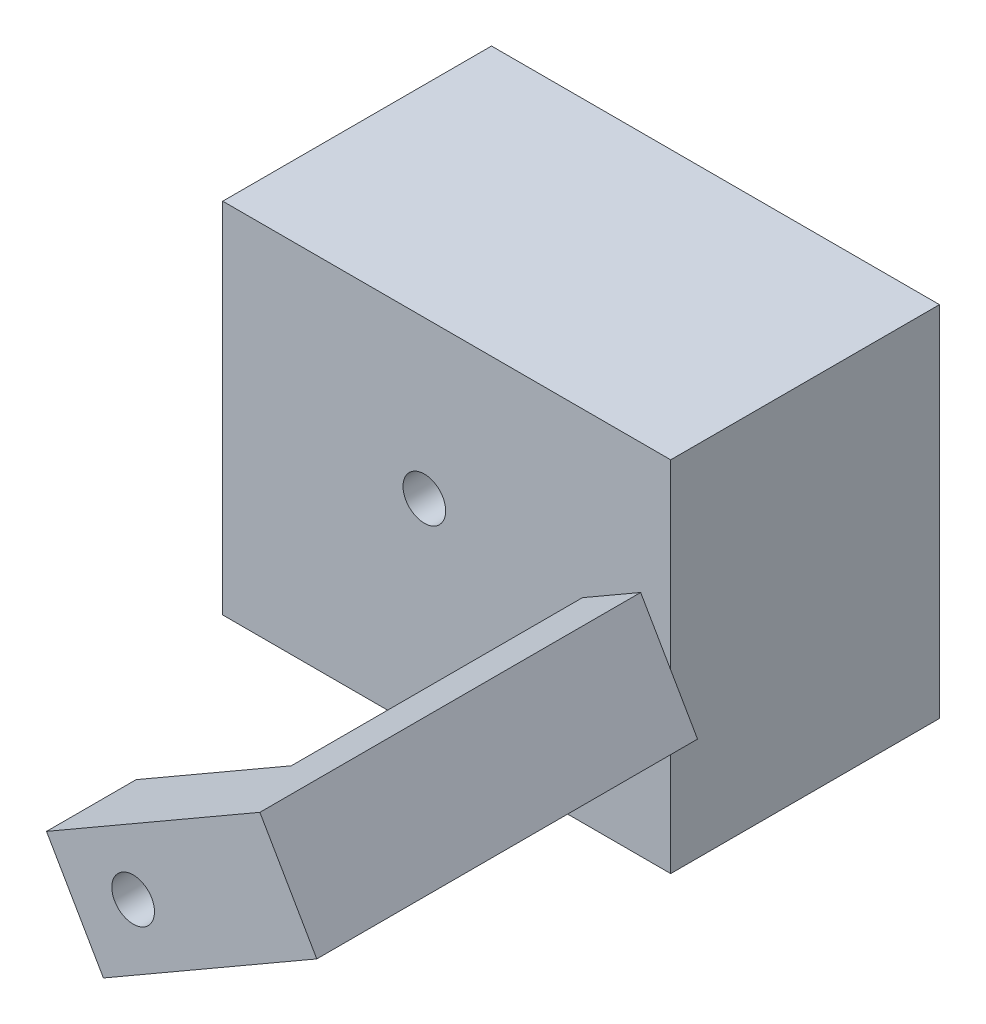
SolidWorks part; units mm, degrees
ref_plane "Front Plane" through (0, 0, 0) normal (0, 0, 1) x (1, 0, 0)
ref_plane "Top Plane" through (0, 0, 0) normal (0, 1, 0) x (1, 0, 0)
ref_plane "Right Plane" through (0, 0, 0) normal (1, 0, 0) x (0, 0, -1)
sketch "Sketch1" plane through (0, 0, 0) normal (0, 1, 0) x (1, 0, 0)
  line L1 (50, -30) -> (-50, -30)
  line L2 (50, -30) -> (50, 30)
  line L3 (50, 30) -> (-50, 30)
  line L4 (-50, -30) -> (-50, 30)
  point P4 (0, 30)
  point P6 (-50, 0)
  dimension "D1" = 100
  dimension "D2" = 60
extrude "Boss-Extrude1" add sketch "Sketch1" along normal mid plane 80
sketch "Sketch2" plane through (0, 0, 30) normal (0, 0, 1) x (1, 0, 0)
  line L0 (-50, -20) -> (50, -20) construction
  line L1 (-50, 40) -> (-50, -40) construction
  line L2 (50, 40) -> (50, -40) construction
  line L3 (-50, -40) -> (50, -40) construction
  line L4 (15, 40) -> (15, -40) construction
  line L5 (-50, 40) -> (50, 40) construction
  line L6 (43.291, 10.9985) -> (30.3006, 3.4985)
  line L7 (30.3006, 3.4985) -> (43.0006, -18.4985)
  line L8 (43.0006, -18.4985) -> (55.991, -10.9985)
  line L9 (55.991, -10.9985) -> (43.291, 10.9985)
  line L10 (15, -20) -> (58.3013, 5) construction
  point P18 (0, 0)
  point P19 (36.6506, -7.5)
  dimension "D1" = 20
  dimension "D2" = 35
  dimension "D3" = 60
  dimension "D4" = 30
  dimension "D5" = 15
  dimension "D6" = 25.4
  dimension "D7" = 25
extrude "Boss-Extrude2" add sketch "Sketch2" along normal blind 85
sketch "Sketch3" plane through (0, 0, 30) normal (0, 0, 1) x (1, 0, 0)
  line L0 (50, -14.4574) -> (50, -40) construction
  line L1 (-50, -40) -> (50, -40) construction
  circle A0 centre (15, -20) radius 4.7625
  point P2 (0, 0)
  point P7 (15.4926, -20.8242)
  dimension "D3" = 9.525
  dimension "D1" = 35
  dimension "D2" = 20
extrude "Cut-Extrude1" cut sketch "Sketch3" against normal through all both and the other way through all
sketch "Sketch5" plane through (24.2404, 13.9952, 0) normal (-0.866, -0.5, 0) x (0, 0, 1)
  line L0 (115, -12.1205) -> (30, -12.1205) construction
  line L1 (115, -37.5205) -> (95, -37.5205)
  line L2 (115, -37.5205) -> (115, -12.1205)
  line L3 (115, -12.1205) -> (95, -12.1205)
  line L4 (95, -37.5205) -> (95, -12.1205)
  dimension "D1" = 20
extrude "Boss-Extrude3" add sketch "Sketch5" along normal blind 40
sketch "Sketch4" plane through (0, 0, 30) normal (0, 0, 1) x (1, 0, 0)
  line L0 (50, 5) -> (-50, 5) construction
  line L1 (50, -14.4574) -> (50, -40) construction
  line L2 (-50, 40) -> (-50, -40) construction
  line L3 (-5, 40) -> (-5, -40) construction
  line L4 (-50, 40) -> (50, 40) construction
  line L5 (-50, -40) -> (50, -40) construction
  circle A0 centre (15, -20) radius 4.7625 construction
  circle A1 centre (-5, 5) radius 4.7625
  point P16 (0, 0)
  dimension "D2" = 20
  dimension "D1" = 25
extrude "Cut-Extrude2" cut sketch "Sketch4" against normal through all both
sketch "Sketch6" plane through (0, 0, 95) normal (0, 0, -1) x (-1, 0, 0)
  circle A0 centre (-15, -20) radius 4.7625
  dimension "D1" = 9.525
extrude "Cut-Extrude3" cut sketch "Sketch6" against normal blind 40
